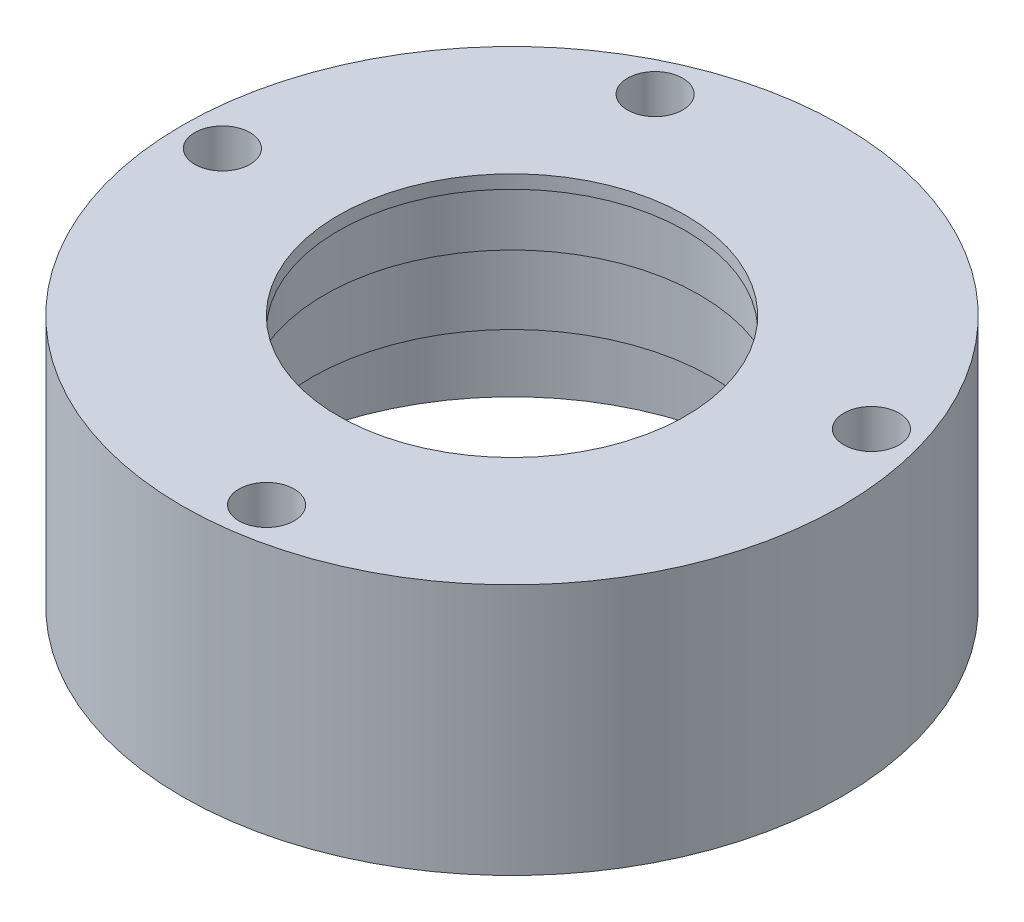
SolidWorks part; units mm, degrees
ref_plane "Front Plane" through (0, 0, 0) normal (0, 0, 1) x (1, 0, 0)
ref_plane "Top Plane" through (0, 0, 0) normal (0, 1, 0) x (1, 0, 0)
ref_plane "Right Plane" through (0, 0, 0) normal (1, 0, 0) x (0, 0, -1)
sketch "Sketch1" plane through (0, 0, 0) normal (0, 1, 0) x (1, 0, 0)
  circle A0 centre (0, 0) radius 37
  dimension "D1" = 74
extrude "Boss-Extrude1" add sketch "Sketch1" along normal blind 28.25
sketch "Sketch2" plane through (0, 0, 0) normal (0, 1, 0) x (1, 0, 0)
  circle A0 centre (0, 0) radius 28.8
  dimension "D1" = 57.6
extrude "Cut-Extrude1" cut sketch "Sketch2" along normal blind 11
sketch "Sketch3" plane through (0, 11, 0) normal (0, -1, 0) x (1, 0, 0)
  circle A0 centre (0, 0) radius 22.5
  dimension "D1" = 45
extrude "Cut-Extrude2" cut sketch "Sketch3" against normal blind 8.75
sketch "Sketch4" plane through (0, 19.75, 0) normal (0, -1, 0) x (1, 0, 0)
  circle A0 centre (0, 0) radius 21.05
  dimension "D1" = 42.1
extrude "Cut-Extrude3" cut sketch "Sketch4" against normal blind 7
sketch "Sketch5" plane through (0, 26.75, 0) normal (0, -1, 0) x (1, 0, 0)
  circle A0 centre (0, 0) radius 19.5
  dimension "D1" = 39
extrude "Cut-Extrude4" cut sketch "Sketch5" against normal through all
sketch "Sketch6" plane through (0, 0, 0) normal (0, 1, 0) x (1, 0, 0)
  line L0 (-15.5375, 0) -> (15.5375, 0) construction
  circle A0 centre (27, 0) radius 1.675
  dimension "D1" = 3.35
  dimension "D2" = 27
extrude "Cut-Extrude5" cut sketch "Sketch6" along normal blind 15.75
pattern_circular "CirPattern1" count 11 over 360 about axis through (0, 0, 0) along (0, 1, 0) of "Cut-Extrude5"
sketch "Sketch7" plane through (0, 0, 0) normal (0, 1, 0) x (1, 0, 0)
  line L0 (0, 0) -> (43.5659, 0) construction
  line L1 (0, 0) -> (39.8091, 11.6863) construction
  line L2 (0, 0) -> (-18.3308, 40.1305) construction
  line L3 (0, 0) -> (-43.804, 0) construction
  line L4 (0, 0) -> (6.4033, -44.546) construction
  circle A0 centre (31.1841, 9.1543) radius 1.7
  circle A1 centre (-13.5033, 29.562) radius 1.7
  circle A2 centre (-32.5, 0) radius 1.7
  circle A3 centre (4.6242, -32.1693) radius 1.7
  dimension "D5" = 3.4
  dimension "D6" = 3.4
  dimension "D7" = 3.4
  dimension "D8" = 3.4
  dimension "D1" = 16.36
  dimension "D2" = 114.55
  dimension "D3" = 180
  dimension "D4" = 278.18
  dimension "D9" = 32.5
  dimension "D10" = 32.5
  dimension "D11" = 32.5
  dimension "D12" = 32.5
extrude "Cut-Extrude6" cut sketch "Sketch7" along normal through all
sketch "Sketch8" plane through (0, 28.25, 0) normal (0, 1, 0) x (1, 0, 0)
  circle A0 centre (31.1841, 9.1543) radius 3.1
  circle A1 centre (-13.5033, 29.562) radius 3.1
  circle A2 centre (-32.5, 0) radius 3.1
  circle A3 centre (4.6242, -32.1693) radius 3.1
  dimension "D1" = 6.2
  dimension "D2" = 6.2
  dimension "D3" = 6.2
  dimension "D4" = 6.2
extrude "Cut-Extrude7" cut sketch "Sketch8" against normal blind 16.75
equation "\"pin_circle_R\" = 27"
equation "\"ecc\" = 1.5"
equation "\"n_pins\" = 11"
equation "\"pin_d\" = 3"
equation "\"out_pin_R\" = 18.5"
equation "\"disc_clr\" = 0.1"
equation "\"seat_6803\" = 26.02"
equation "\"seat_6806\" = 42.1"
equation "\"disc_t\" = 5"
equation "\"out_hole_clr\" = 0.7"
equation "\"boss_17\" = 17.15"
equation "\"rotor_bolt_R\" = 10"
equation "\"m25_clr\" = 2.8"
equation "\"m25_head\" = 5"
equation "\"insert_hole\" = 4.4"
equation "\"csk\" = 0.6"
equation "\"peg_d\" = 3.0"
equation "\"plug_d\" = 8.6"
equation "\"peg_clr\" = 0.3"
equation "\"m3_clr\" = 3.4"
equation "\"m3_head\" = 6.2"
equation "\"pin_press\" = 3.2"
equation "\"pin_slip\" = 3.35"
equation "\"hub_30\" = 30.20"
equation "\"hub_short\" = 0.2"
equation "\"m3_tap\" = 2.8"
equation "\"rear_plate_t\" = 2"
equation "\"motor_ring\" = 40.4"
equation "\"D1@Sketch4\"=\"seat_6806\""
equation "\"D1@Sketch6\"=\"pin_slip\""
equation "\"D2@Sketch6\"=\"pin_circle_R\""
equation "\"D1@CirPattern1\"=\"n_pins\""
equation "\"D5@Sketch7\"=\"m3_clr\""
equation "\"D6@Sketch7\"=\"m3_clr\""
equation "\"D7@Sketch7\"=\"m3_clr\""
equation "\"D8@Sketch7\"=\"m3_clr\""
equation "\"D1@Sketch8\"=\"m3_head\""
equation "\"D2@Sketch8\"=\"m3_head\""
equation "\"D3@Sketch8\"=\"m3_head\""
equation "\"D4@Sketch8\"=\"m3_head\""
equation "\"plug_shaft_d\" = 8.8"
